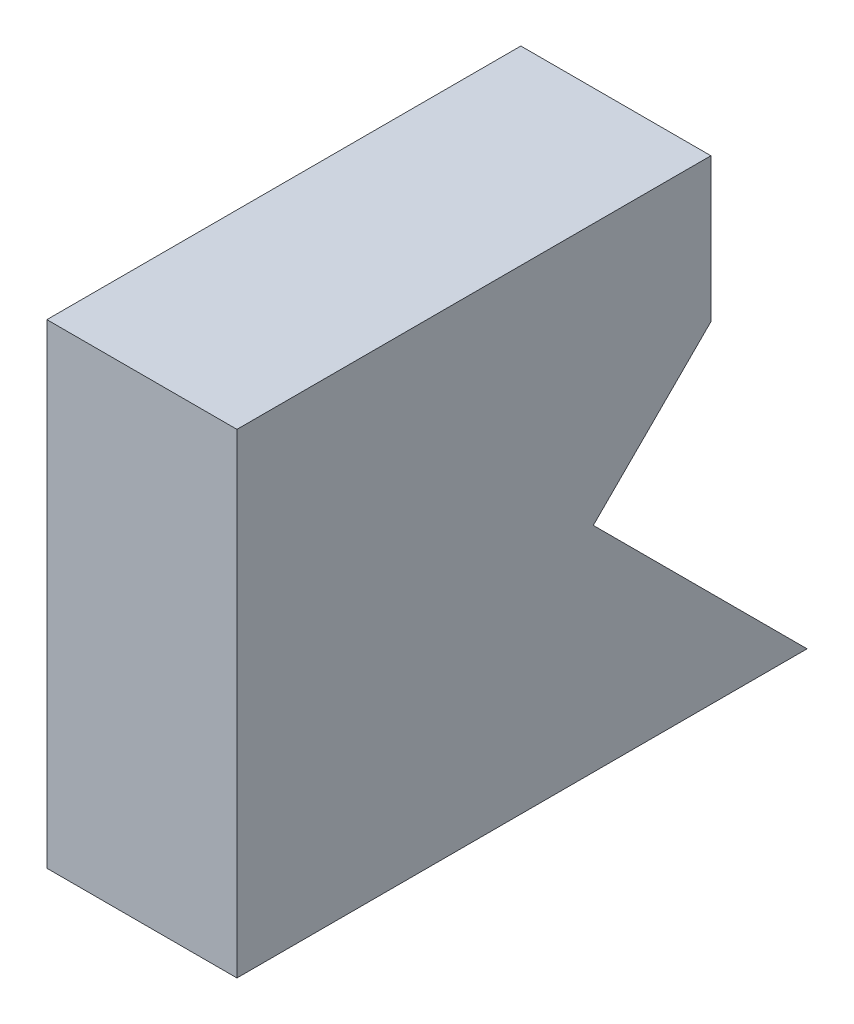
SolidWorks part; units mm, degrees
ref_plane "Plan de face" through (0, 0, 0) normal (0, 0, 1) x (1, 0, 0)
ref_plane "Plan de dessus" through (0, 0, 0) normal (0, 1, 0) x (1, 0, 0)
ref_plane "Plan de droite" through (0, 0, 0) normal (1, 0, 0) x (0, 0, -1)
sketch "Esquisse1" plane through (0, 0, 0) normal (1, 0, 0) x (0, 0, -1)
  line L0 (0, 0) -> (-120, 0)
  line L1 (-120, 0) -> (-120, 100)
  line L2 (-120, 100) -> (-20.2513, 100)
  line L3 (-20.2513, 100) -> (-20.2513, 69.7487)
  line L4 (-20.2513, 69.7487) -> (-45, 45)
  line L5 (-45, 45) -> (0, 0)
  point P3 (-81.3622, 70.9439)
  point P8 (-93.9938, 58.6997)
  point P9 (-43.4675, 83.9628)
  point P10 (0, 0)
  dimension "D1" = 120
  dimension "D2" = 100
  dimension "D3" = 35
  dimension "D4" = 75
  dimension "D5" = 45
extrude "Boss.-Extru.1" add sketch "Esquisse1" along normal blind 40
